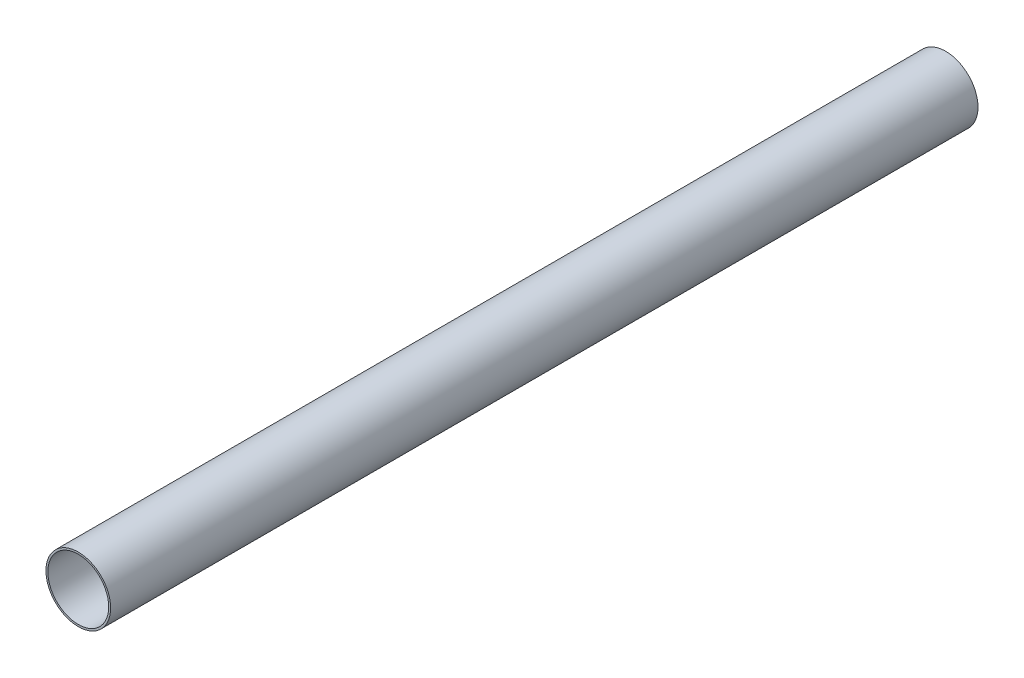
SolidWorks part; units mm, degrees
material "Silicon Rubber"
ref_plane "Front Plane" through (0, 0, 0) normal (0, 0, 1) x (1, 0, 0)
ref_plane "Top Plane" through (0, 0, 0) normal (0, 1, 0) x (1, 0, 0)
ref_plane "Right Plane" through (0, 0, 0) normal (1, 0, 0) x (0, 0, -1)
sketch "Sketch1" plane through (0, 0, 0) normal (0, 0, 1) x (1, 0, 0)
  circle A0 centre (0, 0) radius 26.9875
  circle A1 centre (0, 0) radius 25.4
  dimension "D1" = 50.8
  dimension "D2" = 1.5875
extrude "Boss-Extrude1" add sketch "Sketch1" along normal blind 723.9
